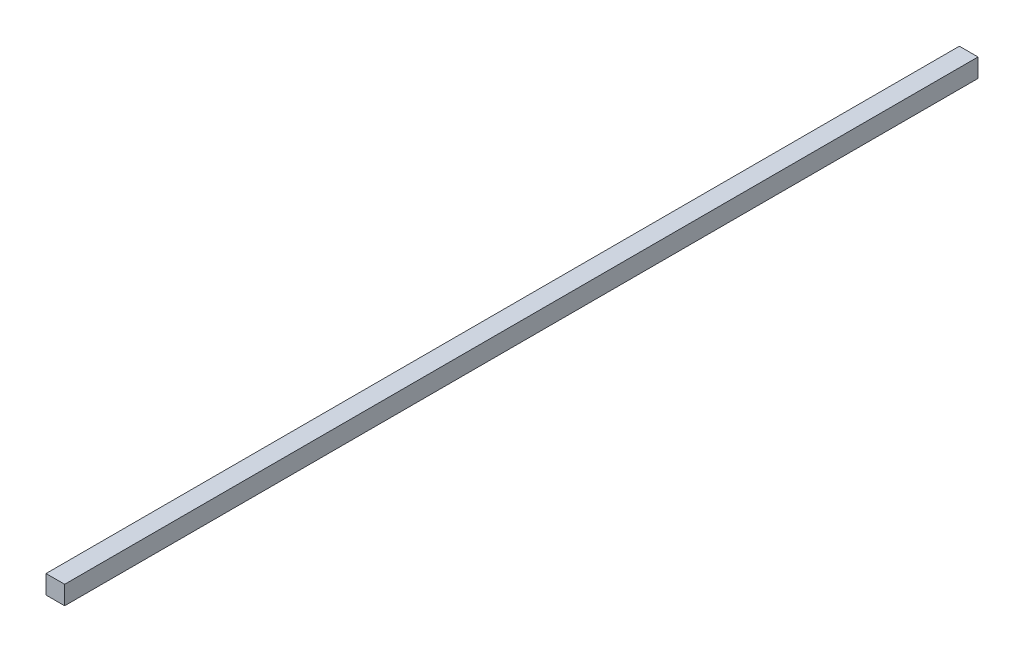
SolidWorks part; units mm, degrees
ref_plane "Front Plane" through (0, 0, 0) normal (0, 0, 1) x (1, 0, 0)
ref_plane "Top Plane" through (0, 0, 0) normal (0, 1, 0) x (1, 0, 0)
ref_plane "Right Plane" through (0, 0, 0) normal (1, 0, 0) x (0, 0, -1)
sketch "Sketch1" plane through (0, 0, 0) normal (0, 0, 1) x (1, 0, 0)
  line L1 (-7.4194, 6.5323) -> (2.5806, 6.5323)
  line L2 (-7.4194, 6.5323) -> (-7.4194, -3.4677)
  line L3 (-7.4194, -3.4677) -> (2.5806, -3.4677)
  line L4 (2.5806, 6.5323) -> (2.5806, -3.4677)
  dimension "D1" = 10
  dimension "D2" = 10
extrude "Boss-Extrude1" add sketch "Sketch1" along normal blind 490
